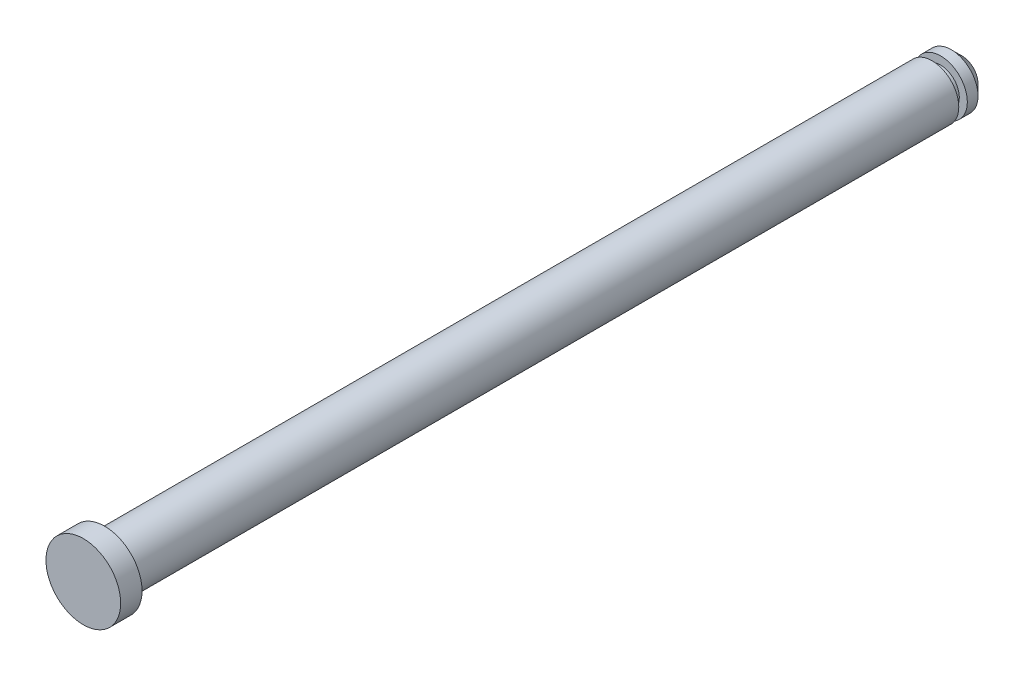
SolidWorks part; units mm, degrees
material "普通碳钢"
ref_plane "前视基准面" through (0, 0, 0) normal (0, 0, 1) x (1, 0, 0)
ref_plane "上视基准面" through (0, 0, 0) normal (0, 1, 0) x (1, 0, 0)
ref_plane "右视基准面" through (0, 0, 0) normal (1, 0, 0) x (0, 0, -1)
sketch "草图1" plane through (0, 0, 0) normal (1, 0, 0) x (0, 0, -1)
  line L0 (79.5, 2.5) -> (2, 2.5)
  line L1 (0, 0) -> (82.3, 0)
  line L2 (0, 0) -> (0, 3.5)
  line L3 (0, 3.5) -> (2, 3.5)
  line L4 (82.3, 0) -> (82.3, 2.5)
  line L5 (0, 0) -> (79.4705, 0) construction
  line L7 (82.3, 2.5) -> (80.3, 2.5)
  line L8 (2, 3.5) -> (2, 2.5)
  line L10 (79.5, 2.5) -> (79.5, 1.75)
  line L11 (79.5, 1.75) -> (80.3, 1.75)
  line L12 (80.3, 2.5) -> (80.3, 1.75)
  dimension "D1" = 2.5
  dimension "D2" = 3.5
  dimension "D3" = 2
  dimension "D4" = 77.5
  dimension "D5" = 2
  dimension "D6" = 0.8
  dimension "D7" = 1.75
revolve "旋转1" add sketch "草图1" angle 360 about L5
chamfer "倒角1" distance 1 angle 45 1 edges at (2.5, 0, -82.3)
